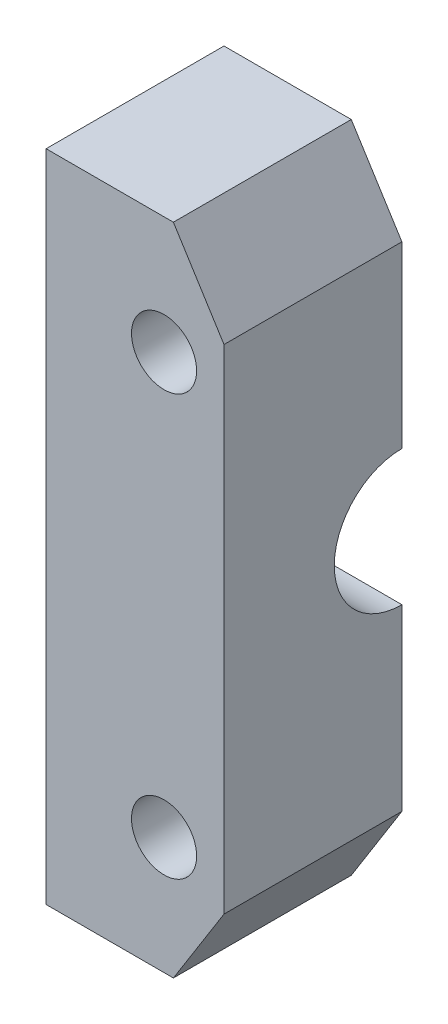
SolidWorks part; units mm, degrees
material "6061 Alloy"
ref_plane "Front Plane" through (0, 0, 0) normal (0, 0, 1) x (1, 0, 0)
ref_plane "Top Plane" through (0, 0, 0) normal (0, 1, 0) x (1, 0, 0)
ref_plane "Right Plane" through (0, 0, 0) normal (1, 0, 0) x (0, 0, -1)
sketch "Sketch1" plane through (0, 0, 0) normal (0, 0, 1) x (1, 0, 0)
  line L1 (81.54, 23.365) -> (94.24, 23.365)
  line L2 (81.54, 23.365) -> (81.54, -23.365)
  line L3 (81.54, -23.365) -> (94.24, -23.365)
  line L4 (94.24, 23.365) -> (94.24, -23.365)
  line L9 (94.24, 4.826) -> (94.24, 17.6074)
  line L10 (94.24, 17.6074) -> (90.6266, 23.365)
  line L11 (77.2278, 38.2924) -> (72.7482, 36.0713)
  line L12 (72.7482, -36.0713) -> (77.2278, -38.2924)
  line L13 (90.6266, -23.365) -> (94.24, -17.6074)
  line L14 (94.24, -17.6074) -> (94.24, -4.826)
  line L15 (94.24, -4.826) -> (86.49, -4.826)
  line L16 (86.49, -4.826) -> (86.49, 4.826)
  line L17 (86.49, 4.826) -> (94.24, 4.826)
  line L18 (94.24, 4.826) -> (94.24, 17.6074)
  line L19 (94.24, 17.6074) -> (90.6266, 23.365)
  line L20 (77.2278, 38.2924) -> (72.7482, 36.0713)
  line L21 (72.7482, -36.0713) -> (77.2278, -38.2924)
  line L22 (90.6266, -23.365) -> (94.24, -17.6074)
  line L23 (94.24, -17.6074) -> (94.24, -4.826)
  line L24 (94.24, -4.826) -> (86.49, -4.826)
  line L25 (86.49, -4.826) -> (86.49, 4.826)
  line L26 (86.49, 4.826) -> (94.24, 4.826)
  circle A2 centre (89.96, 15) radius 2.325
  arc A3 (77.2278, 38.2924) -> (90.6266, 23.365) centre (110.7726, 54.9252) ccw
  arc A4 (72.7482, -36.0713) -> (72.7482, 36.0713) centre (0, 0) ccw
  arc A5 (90.6266, -23.365) -> (77.2278, -38.2924) centre (110.7726, -54.9252) ccw
  arc A6 (77.2278, 38.2924) -> (90.6266, 23.365) centre (110.7726, 54.9252) ccw
  arc A7 (72.7482, -36.0713) -> (72.7482, 36.0713) centre (0, 0) ccw
  arc A8 (90.6266, -23.365) -> (77.2278, -38.2924) centre (110.7726, -54.9252) ccw
  circle A9 centre (89.96, -15) radius 2.325
  circle A10 centre (89.96, 15) radius 2.5527 construction
  circle A11 centre (89.96, -15) radius 2.5527 construction
  dimension "D2" = 12.7
  dimension "D1" = 0
extrude "Boss-Extrude1" add sketch "Sketch1" along normal blind 12.7 contours L25 L26 L4 L19 L1 L2 L3 L22 L24 A9 A2 | L26 L25 L24 L4
sketch "Sketch2" plane through (94.24, 0, 0) normal (1, 0, 0) x (0, 0, -1)
  line L4 (0, -17.6074) -> (0, 17.6074)
  line L5 (0, 17.6074) -> (-12.7, 17.6074)
  line L6 (-12.7, 17.6074) -> (-12.7, -17.6074)
  line L7 (-12.7, -17.6074) -> (0, -17.6074)
  line L8 (0, -17.6074) -> (0, 17.6074)
  line L9 (0, 17.6074) -> (-12.7, 17.6074)
  line L10 (-12.7, 17.6074) -> (-12.7, -17.6074)
  line L11 (-12.7, -17.6074) -> (0, -17.6074)
  arc A0 (0, 4.826) -> (0, -4.826) centre (0, 0) ccw construction
  arc A1 (0, 4.826) -> (0, -4.826) centre (0, 0) ccw
  circle A2 centre (0, 0) radius 4.826
  dimension "D1" = 0
extrude "Cut-Extrude1" cut sketch "Sketch2" against normal blind 8 contours A2
